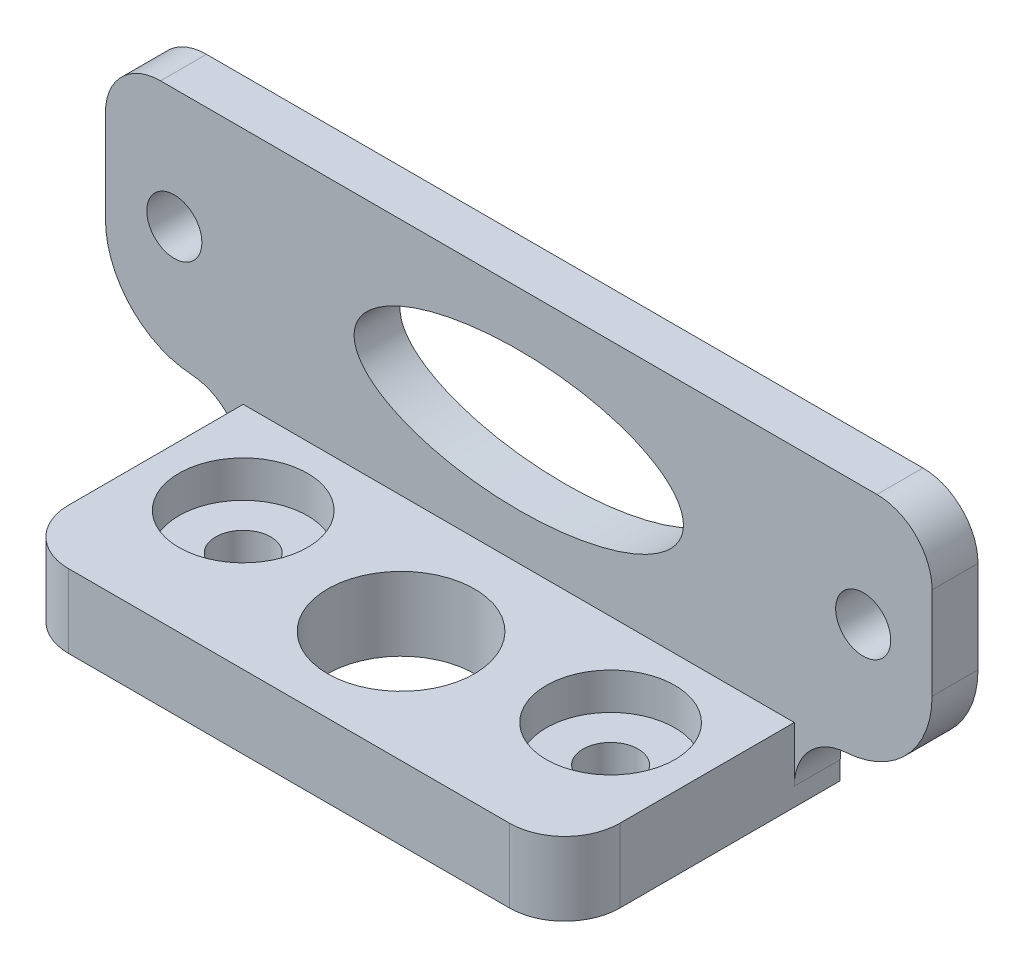
SolidWorks part; units mm, degrees
ref_plane "前视基准面" through (0, 0, 0) normal (0, 0, 1) x (1, 0, 0)
ref_plane "上视基准面" through (0, 0, 0) normal (0, 1, 0) x (1, 0, 0)
ref_plane "右视基准面" through (0, 0, 0) normal (1, 0, 0) x (0, 0, -1)
sketch "草图1" plane through (0, 0, 0) normal (0, 1, 0) x (1, 0, 0)
  line L1 (-15, 7.5) -> (15, 7.5)
  line L2 (-15, 7.5) -> (-15, -7.5)
  line L3 (-15, -7.5) -> (15, -7.5)
  line L4 (15, 7.5) -> (15, -7.5)
  line L5 (-15, 7.5) -> (15, -7.5) construction
  line L6 (-15, -7.5) -> (15, 7.5) construction
  point P0 (0, 0)
extrude "凸台-拉伸1" add sketch "草图1" along normal blind 4
sketch "草图2" plane through (0, 4, 0) normal (0, 1, 0) x (1, 0, 0)
  line L0 (0, 7.5) -> (0, 6.25) construction
  line L1 (15, 7.5) -> (-15, 7.5) construction
  line L3 (-22.5, 7.5) -> (22.5, 7.5)
  line L4 (-22.5, 7.5) -> (-22.5, 5)
  line L5 (-22.5, 5) -> (22.5, 5)
  line L6 (22.5, 7.5) -> (22.5, 5)
  line L7 (-22.5, 7.5) -> (22.5, 5) construction
  line L8 (-22.5, 5) -> (22.5, 7.5) construction
  dimension "D1" = 1.25
  dimension "D2" = 2.5
  dimension "D3" = 45
extrude "凸台-拉伸2" add sketch "草图2" along normal blind 13
sketch "草图3" plane through (0, 0, -5) normal (0, 0, 1) x (1, 0, 0)
  line L0 (0, 17) -> (0, 4) construction
  line L1 (-22.5, 17) -> (22.5, 17) construction
  line L2 (-15, 4) -> (15, 4) construction
  line L3 (15, 4) -> (22.5, 4) construction
  circle A0 centre (18.75, 10.5) radius 1.5
  circle A1 centre (-18.75, 10.5) radius 1.5
  dimension "D1" = 37.5
  dimension "D2" = 6.5
extrude "切除-拉伸1" cut sketch "草图3" against normal blind 25
fillet "圆角1" radius 3 6 edges at (-15, 2, 7.5) (15, 2, 7.5) (-22.5, 17, -6.25) (22.5, 17, -6.25)
sketch "草图4" plane through (0, 4, 0) normal (0, 1, 0) x (1, 0, 0)
  line L0 (0, 0) -> (10, 0) construction
  line L1 (0, 0) -> (-10, 0) construction
  circle A0 centre (10, 0) radius 1.5
  circle A1 centre (-10, 0) radius 1.5
  dimension "D1" = 20
  dimension "D2" = 10
extrude "切除-拉伸2" cut sketch "草图4" against normal blind 25 contours A0 | A1
sketch "草图5" plane through (0, 4, 0) normal (0, 1, 0) x (1, 0, 0)
  circle A0 centre (10, 0) radius 3.5
  circle A1 centre (-10, 0) radius 3.5
extrude "切除-拉伸3" cut sketch "草图5" against normal blind 2
fillet "圆角2" radius 5 2 edges at (-22.5, 4, -6.25) (22.5, 4, -6.25)
sketch "草图6" plane through (0, 0, -5) normal (0, 0, 1) x (1, 0, 0)
  ellipse E0 centre (0, 10.284) end of major axis (8.9621, 10.284) minor radius 3.7779
extrude "切除-拉伸4" cut sketch "草图6" against normal blind 10
sketch "草图7" plane through (0, 4, 0) normal (0, 1, 0) x (1, 0, 0)
  circle A0 centre (0, -1.4062) radius 4
extrude "切除-拉伸5" cut sketch "草图7" against normal blind 10
